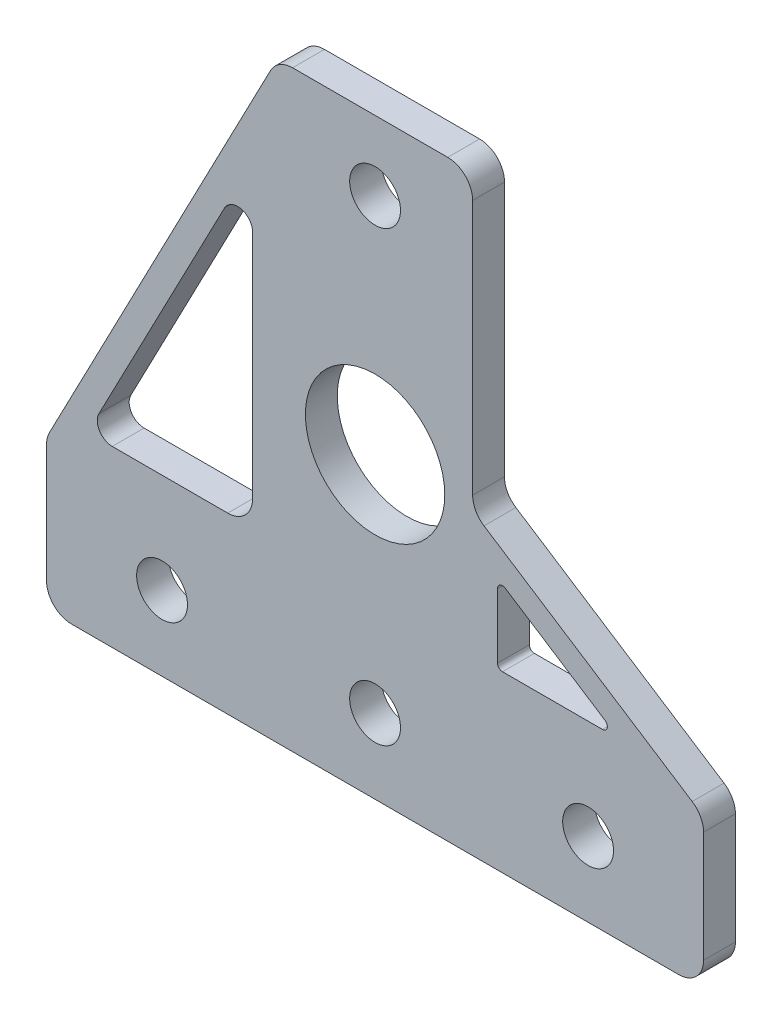
SolidWorks part; units mm, degrees
material "6061-T6 (SS)"
ref_plane "Front Plane" through (0, 0, 0) normal (0, 0, 1) x (1, 0, 0)
ref_plane "Top Plane" through (0, 0, 0) normal (0, 1, 0) x (1, 0, 0)
ref_plane "Right Plane" through (0, 0, 0) normal (1, 0, 0) x (0, 0, -1)
sketch "Sketch1" plane through (0, 0, 0) normal (0, 0, 1) x (1, 0, 0)
  line L0 (9.8, 25) -> (-9.8, 25)
  line L1 (33, 69.5) -> (-14.75, 69.5) construction
  line L2 (9.8, 10) -> (-9.8, 10)
  line L3 (9.8, 25) -> (9.8, 10)
  line L4 (-9.8, 25) -> (-9.8, 10)
  line L5 (0, 10) -> (0, 25) construction
  line L6 (9.8, 69.5) -> (-9.8, 69.5)
  line L12 (33, 69.5) -> (-14.75, 69.5) construction
  line L14 (9.8, 25) -> (9.8, 69.5)
  line L15 (-9.8, 25) -> (-9.8, 69.5)
  circle A0 centre (0, 17.5) radius 2.5527 construction
  circle A1 centre (0, 17.5) radius 2.5527
  circle A2 centre (0, 40) radius 7 construction
  circle A3 centre (0, 40) radius 7
  circle A5 centre (0, 62.5) radius 2.5527
  dimension "D2" = 19.6
  dimension "D1" = 15
extrude "Boss-Extrude1" add sketch "Sketch1" along normal blind 3.2
sketch "Sketch2" plane through (0, 0, 3.2) normal (0, 0, 1) x (1, 0, 0)
  line L0 (-33, 10) -> (-33, 25) construction
  line L1 (-33, 10) -> (33, 10) construction
  line L2 (33, 10) -> (33, 25) construction
  line L3 (33, 25) -> (-33, 25) construction
  line L4 (9.8, 10) -> (9.8, 69.5) construction
  line L5 (-9.8, 10) -> (-9.8, 69.5) construction
  line L6 (-33, 10) -> (-33, 25)
  line L7 (-33, 10) -> (33, 10)
  line L8 (33, 10) -> (33, 25)
  line L9 (33, 25) -> (9.8, 25)
  line L10 (9.8, 10) -> (9.8, 69.5)
  line L11 (-9.8, 10) -> (-9.8, 69.5)
  line L12 (-33, 25) -> (-9.8, 25)
  circle A0 centre (21.4, 17.5) radius 2.5527 construction
  circle A1 centre (-21.4, 17.5) radius 2.5527 construction
  circle A2 centre (21.4, 17.5) radius 2.5527
  circle A3 centre (-21.4, 17.5) radius 2.5527
  line M9 (9.8, 10) -> (9.8, 69.5)
extrude "T-shape Extension" add sketch "Sketch2" against normal up to surface (3.2 mm away) contours L8 L9 L7 A2 M9 | L12 L6 L7 L11 A3 up to face at (2.5527, 62.5, 0)
ref_plane "Plane1" through (-33, 25, 3.2) normal (1, 0, 0) x (0, 0, -1)
sketch "Sketch8" plane through (0, 0, 3.2) normal (0, 0, 1) x (1, 0, 0)
  line L0 (-33, 25) -> (-9.8, 25) construction
  line L1 (33, 25) -> (9.8, 25) construction
  line L2 (-9.8, 25) -> (-9.8, 69.5) construction
  line L3 (9.8, 25) -> (9.8, 69.5) construction
  line L4 (9.8, 69.5) -> (-9.8, 69.5) construction
  line L5 (-33, 25) -> (-9.8, 25)
  line L6 (33, 25) -> (9.8, 25)
  line L7 (-9.8, 25) -> (-9.8, 69.5)
  line L8 (9.8, 25) -> (9.8, 69.5) construction
  line L9 (9.8, 69.5) -> (-9.8, 69.5)
  line L10 (0, 40) -> (9.8, 40) construction
  line L11 (9.8, 40) -> (33, 25)
  line L12 (0, 40) -> (-9.8, 40) construction
  line L13 (-9.8, 40) -> (-33, 25) construction
  line L14 (-9.8, 47) -> (9.8, 47)
  line L16 (-9.8, 69.5) -> (-33, 25)
  line L18 (9.8, 25) -> (9.8, 47.25) construction
  line L22 (-12.3, 27.5) -> (-12.3, 59.2969)
  line L23 (-12.3, 59.2969) -> (-28.8773, 27.5)
  line L27 (-28.8773, 27.5) -> (-12.3, 27.5)
  line L28 (9.8, 40) -> (9.8, 25)
  line L29 (12.3, 35.4066) -> (24.5289, 27.5)
  line L30 (24.5289, 27.5) -> (12.3, 27.5)
  line L31 (12.3, 35.4066) -> (12.3, 27.5)
  circle A0 centre (0, 40) radius 7 construction
  circle A1 centre (0, 40) radius 7
  point P14 (0, 47)
  dimension "D1" = 2.5
  dimension "D2" = 2.5
extrude "Asymmetric Triangle Supports" add sketch "Sketch8" against normal up to surface (3.2 mm away)
fillet "Fillet1" radius 1.5 2 edges at (-12.3, 59.2969, 1.6) (-28.8773, 27.5, 1.6)
fillet "Fillet2" radius 2.5 1 edges at (-12.3, 27.5, 1.6)
fillet "Fillet3" radius 0.5 3 edges at (24.5289, 27.5, 1.6) (12.3, 35.4066, 1.6) (12.3, 27.5, 1.6)
fillet "Fillet4" radius 2.5 7 edges at (9.8, 69.5, 1.6) (-9.8, 69.5, 1.6) (-33, 10, 1.6) (33, 10, 1.6) (33, 25, 1.6) (9.8, 40, 1.6) (-33, 25, 1.6)
ref_plane "Plane3" through (0, 0, 3.2) normal (0, 0, -1) x (-1, 0, 0)
sketch "Sketch10" plane through (0, 0, 0) normal (0, 0, -1) x (-1, 0, 0)
  circle A0 centre (0, 40) radius 7 construction
  circle A1 centre (0, 40) radius 7
  circle A2 centre (0, 40) radius 7.85
  dimension "D1" = 15.7
split line "Split Line1" [suppressed]
sketch "Sketch11" [suppressed] plane through (0, 0, 3.2) normal (0, 0, -1) x (-1, 0, 0)
  line L1 (-6.7271, 33) -> (6.7271, 33)
  line L2 (-6.7271, 33) -> (-6.7271, 47)
  line L3 (-6.7271, 47) -> (6.7271, 47)
  line L4 (6.7271, 33) -> (6.7271, 47)
  line L5 (-6.7271, 33) -> (6.7271, 47) construction
  line L6 (-6.7271, 47) -> (6.7271, 33) construction
  circle A0 centre (0, 40) radius 7 construction
  circle A1 centre (0, 40) radius 7
